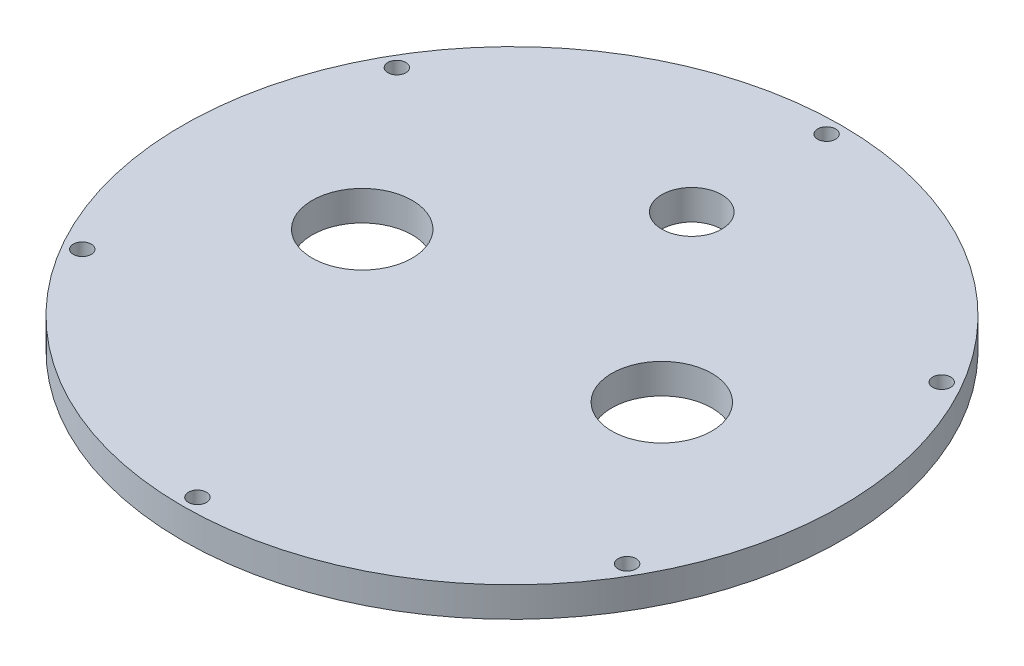
SolidWorks part; units mm, degrees
material "PMMA"
ref_plane "前视基准面" through (0, 0, 0) normal (0, 0, 1) x (1, 0, 0)
ref_plane "上视基准面" through (0, 0, 0) normal (0, 1, 0) x (1, 0, 0)
ref_plane "右视基准面" through (0, 0, 0) normal (1, 0, 0) x (0, 0, -1)
sketch "草图1" plane through (0, 0, 0) normal (0, 1, 0) x (1, 0, 0)
  line L0 (0, 0) -> (98.354, 0) construction
  line L1 (0, 0) -> (0, 95.5765) construction
  circle A0 centre (0, 0) radius 55
  circle A1 centre (0, 0) radius 52.5 construction
  circle A2 centre (0, 52.5) radius 1.5
  circle A3 centre (45.4663, 26.25) radius 1.5
  circle A4 centre (45.4663, -26.25) radius 1.5
  circle A5 centre (0, -52.5) radius 1.5
  circle A6 centre (-45.4663, -26.25) radius 1.5
  circle A7 centre (-45.4663, 26.25) radius 1.5
  point P20 (0, 0)
  point P21 (-35, 0)
  point P24 (35, 0)
  dimension "D1" = 110
  dimension "D2" = 105
  dimension "D3" = 3
  dimension "D5" = 35
  dimension "D4" = 6
extrude "凸台-拉伸1" add sketch "草图1" along normal blind 5
sketch "草图2" plane through (0, 5, 0) normal (0, 1, 0) x (1, 0, 0)
  line L0 (0, 0) -> (100.9585, 0) construction
  line L1 (0, 0) -> (0, 92.4289) construction
  point P3 (-25, 0)
  point P7 (25, 0)
  dimension "D1" = 25
sketch "草图4" plane through (0, 5, 0) normal (0, 1, 0) x (1, 0, 0)
  line L0 (0, 0) -> (0, 30)
  circle A0 centre (0, 30) radius 5
extrude "切除-拉伸1" cut sketch "草图4" against normal blind 10
sketch "草图5" plane through (0, 0, 0) normal (0, -1, 0) x (1, 0, 0)
  circle A0 centre (-25, 0) radius 8.35
  circle A1 centre (25, 0) radius 8.35
  dimension "D1" = 16.7
  dimension "D2" = 16.7
  dimension "D3" = 50
extrude "切除-拉伸2" cut sketch "草图5" against normal through all
sketch "草图7" plane through (0, 0, 0) normal (0, -1, 0) x (1, 0, 0)
  line L0 (0, 0) -> (0, -52.5) construction
  line L1 (-15, -5.7735) -> (-15, 5.7735)
  line L2 (-15, 5.7735) -> (-25, 11.547)
  line L3 (-25, 11.547) -> (-35, 5.7735)
  line L4 (-35, 5.7735) -> (-35, -5.7735)
  line L5 (-35, -5.7735) -> (-25, -11.547)
  line L6 (-25, -11.547) -> (-15, -5.7735)
  line L7 (25, -11.547) -> (15, -5.7735)
  line L8 (35, -5.7735) -> (25, -11.547)
  line L9 (35, 5.7735) -> (35, -5.7735)
  line L10 (25, 11.547) -> (35, 5.7735)
  line L11 (15, 5.7735) -> (25, 11.547)
  line L12 (15, -5.7735) -> (15, 5.7735)
  circle A0 centre (-25, 0) radius 10 construction
  circle A1 centre (25, 0) radius 10 construction
  dimension "D1" = 20
extrude "切除-拉伸3" [suppressed] cut sketch "草图7" against normal blind 3
fillet "圆角1" [suppressed] radius 1.8
